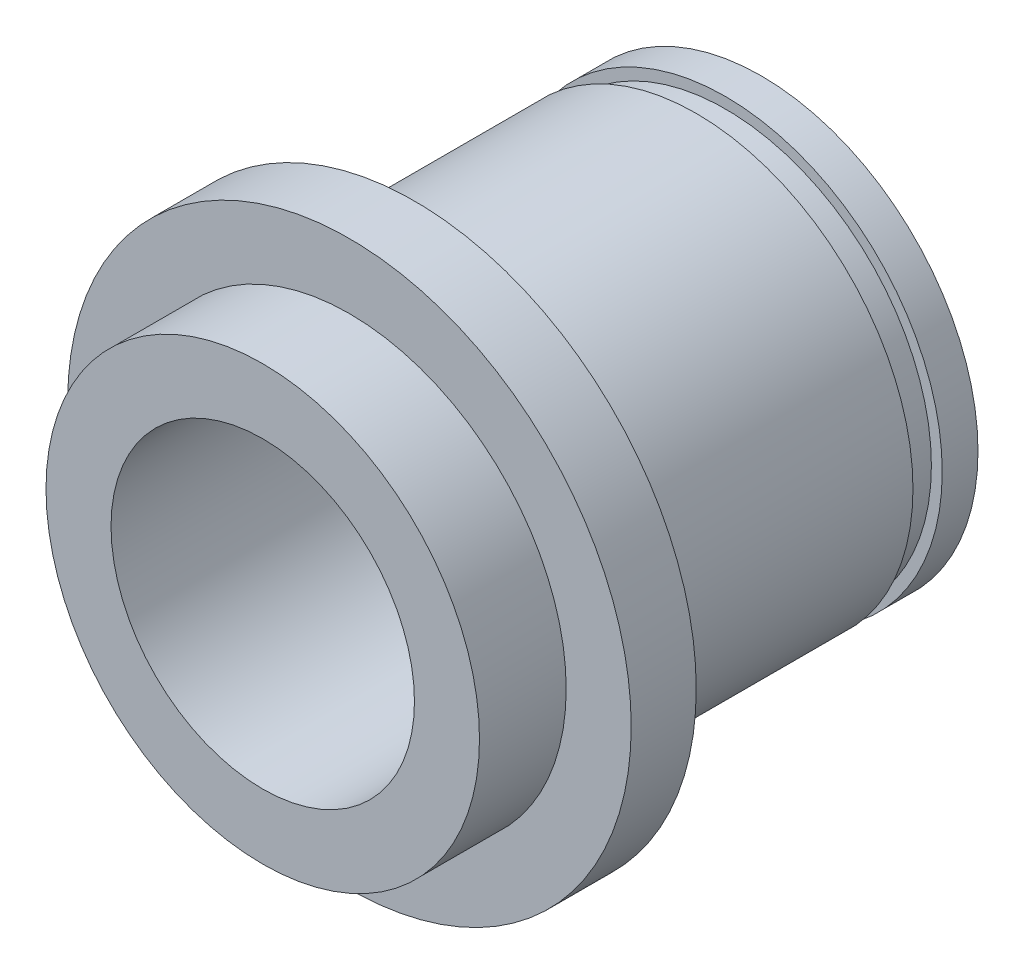
SolidWorks part; units mm, degrees
ref_plane "Front Plane" through (0, 0, 0) normal (1, 0, 0) x (0, 1, 0)
ref_plane "Top Plane" through (0, 0, 0) normal (0, 0, 1) x (0, 1, 0)
ref_plane "Right Plane" through (0, 0, 0) normal (0, 1, 0) x (-1, 0, 0)
sketch "Sketch2" plane through (0, 0, 0) normal (1, 0, 0) x (0, 1, 0)
  line L0 (-17.558, 0) -> (17.4732, 0) construction
  line L1 (0, 15.904) -> (0, -14.971) construction
  line L2 (0, 7) -> (10, 7)
  line L3 (10, 7) -> (10, 3)
  line L4 (10, 3) -> (13, 3)
  line L5 (13, 3) -> (13, 0)
  line L6 (13, 0) -> (10, 0)
  line L7 (10, 0) -> (10, -13)
  line L8 (10, -13) -> (9.5, -13)
  line L9 (9.5, -13) -> (9.5, -14.35)
  line L10 (9.5, -14.35) -> (10, -14.35)
  line L11 (10, -14.35) -> (10, -16)
  line L12 (10, -16) -> (0, -16)
  line L13 (0, 7) -> (0, -16)
  point P12 (9.75, -14.35)
  dimension "D1" = 19
  dimension "D2" = 20
  dimension "D3" = 23
  dimension "D4" = 3
  dimension "D5" = 26
  dimension "D6" = 1.35
  dimension "D7" = 4
  dimension "D8" = 3
revolve "Revolve1" add sketch "Sketch2" angle 360 about L1
sketch "Sketch3" plane through (0, 0, 7) normal (0, 0, 1) x (1, 0, 0)
  circle A0 centre (0, 0) radius 7
  dimension "D1" = 14
extrude "Cut-Extrude1" cut sketch "Sketch3" against normal through all both and the other way through all
